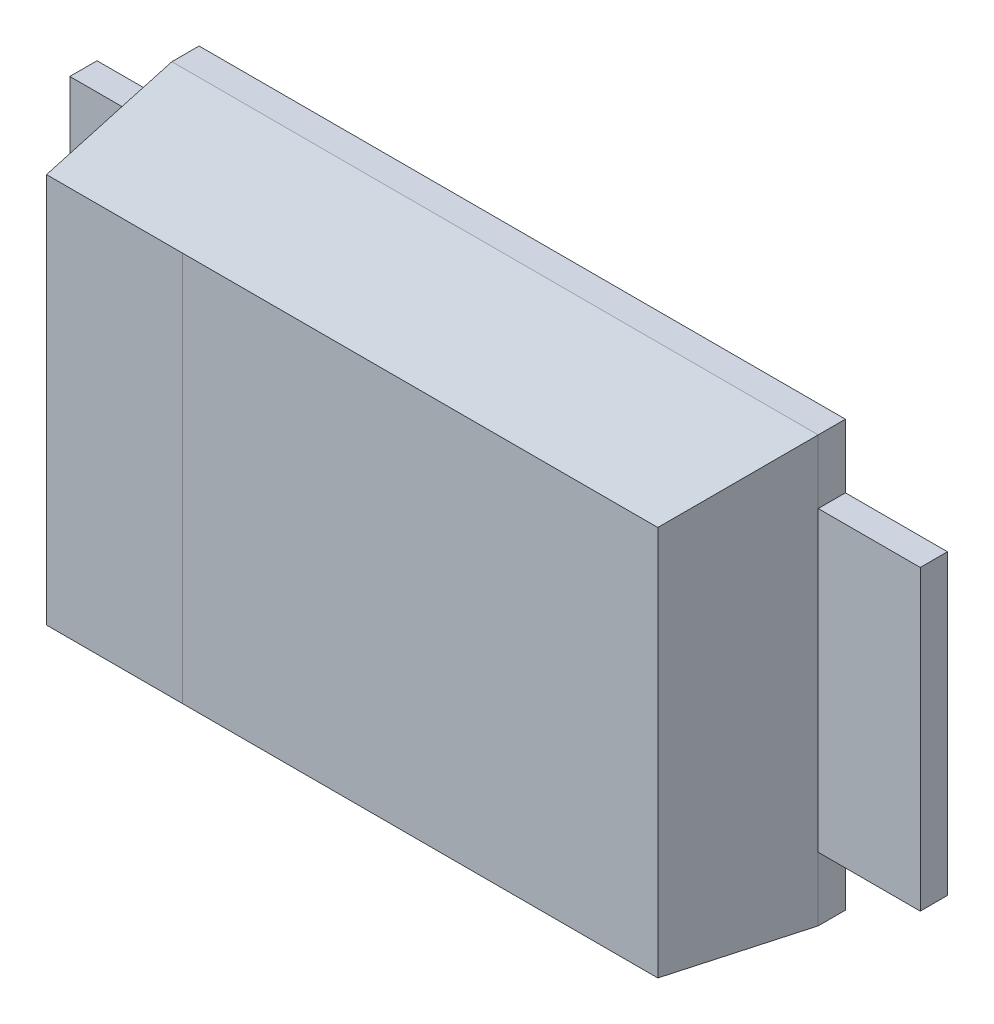
SolidWorks part; units mm, degrees
ref_plane "Plan de face" through (0, 0, 0) normal (0, 0, 1) x (1, 0, 0)
ref_plane "Plan de dessus" through (0, 0, 0) normal (0, 1, 0) x (1, 0, 0)
ref_plane "Plan de droite" through (0, 0, 0) normal (1, 0, 0) x (0, 0, -1)
sketch "Esquisse1" plane through (0, 0, 0) normal (0, 0, 1) x (1, 0, 0)
  line L1 (-1.9, 1.25) -> (1.9, 1.25)
  line L2 (-1.9, 1.25) -> (-1.9, -1.25)
  line L3 (-1.9, -1.25) -> (1.9, -1.25)
  line L4 (1.9, 1.25) -> (1.9, -1.25)
  line L5 (-1.9, 1.25) -> (1.9, -1.25) construction
  line L6 (-1.9, -1.25) -> (1.9, 1.25) construction
  point P0 (0, 0)
  dimension "D1" = 2.5
  dimension "D2" = 3.8
extrude "case base" add sketch "Esquisse1" along normal blind 0.16
sketch "Esquisse2" plane through (0, 0, 0.16) normal (0, 0, 1) x (1, 0, 0)
  line L4 (1.9, -1.25) -> (1.9, 1.25)
  line L5 (1.9, 1.25) -> (-1.9, 1.25)
  line L6 (-1.9, 1.25) -> (-1.9, -1.25)
  line L7 (-1.9, -1.25) -> (1.9, -1.25)
  line L8 (1.9, -1.25) -> (1.9, 1.25)
  line L9 (1.9, 1.25) -> (-1.9, 1.25)
  line L10 (-1.9, 1.25) -> (-1.9, -1.25)
  line L11 (-1.9, -1.25) -> (1.9, -1.25)
  dimension "D1" = 0
extrude "case top" add sketch "Esquisse2" along normal blind 0.84 draft 7
sketch "Esquisse3" plane through (0, 0, 0) normal (0, 0, 1) x (1, 0, 0)
  line L1 (2.5, 0.875) -> (-2.5, 0.875)
  line L2 (2.5, 0.875) -> (2.5, -0.875)
  line L3 (2.5, -0.875) -> (-2.5, -0.875)
  line L4 (-2.5, 0.875) -> (-2.5, -0.875)
  line L5 (2.5, 0.875) -> (-2.5, -0.875) construction
  line L6 (2.5, -0.875) -> (-2.5, 0.875) construction
  point P0 (0, 0)
  dimension "D1" = 1.75
  dimension "D2" = 5
extrude "pins" add sketch "Esquisse3" along normal blind 0.16
sketch "Esquisse4" plane through (0, 0, 1) normal (0, 0, 1) x (1, 0, 0)
  line L0 (-0.9969, 1.1469) -> (-0.9969, -1.1469)
  line L1 (1.7969, 1.1469) -> (-1.7969, 1.1469) construction
  line L2 (-1.7969, -1.1469) -> (1.7969, -1.1469) construction
  line L3 (-1.7969, 1.1469) -> (-1.7969, -1.1469) construction
  dimension "D1" = 0.8
split line "Ligne de séparation1"
